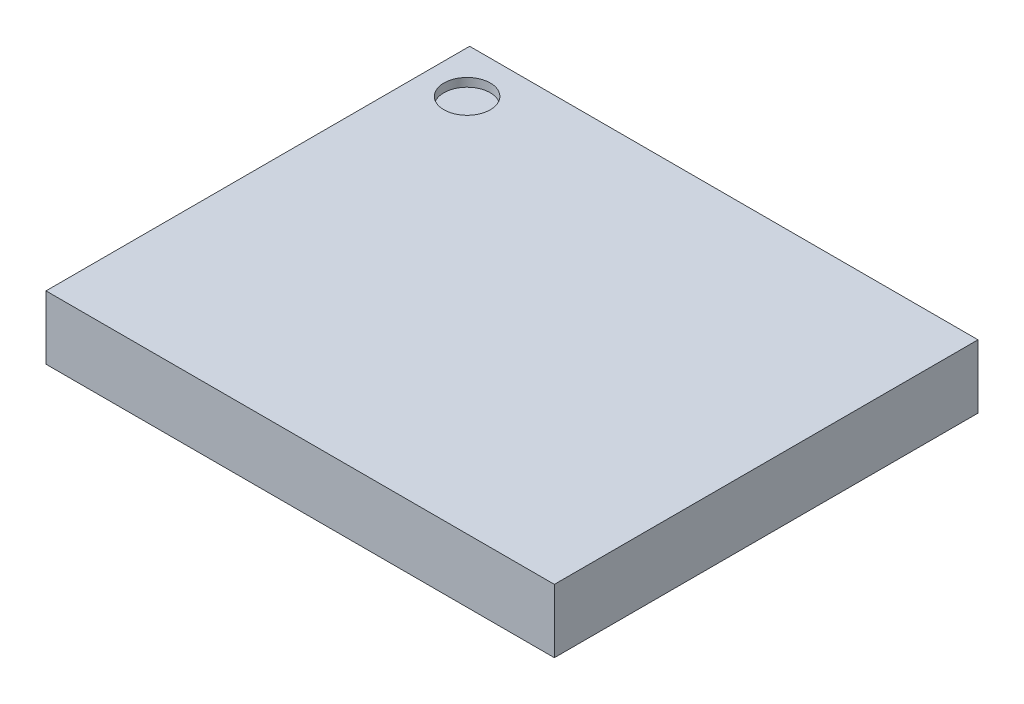
SolidWorks part; units mm, degrees
ref_plane "Front Plane" through (0, 0, 0) normal (0, 0, 1) x (1, 0, 0)
ref_plane "Top Plane" through (0, 0, 0) normal (0, 1, 0) x (1, 0, 0)
ref_plane "Right Plane" through (0, 0, 0) normal (1, 0, 0) x (0, 0, -1)
sketch "Sketch1" plane through (0, 0, 0) normal (0, 1, 0) x (1, 0, 0)
  line L1 (-3, -2.5) -> (3, -2.5)
  line L2 (-3, -2.5) -> (-3, 2.5)
  line L3 (-3, 2.5) -> (3, 2.5)
  line L4 (3, -2.5) -> (3, 2.5)
  line L5 (-3, -2.5) -> (3, 2.5) construction
  line L6 (-3, 2.5) -> (3, -2.5) construction
  point P0 (0, 0)
  dimension "D1" = 6
  dimension "D2" = 5
extrude "Boss-Extrude1" add sketch "Sketch1" along normal blind 0.75
sketch "Sketch2" plane through (0, 0.75, 0) normal (0, 1, 0) x (1, 0, 0)
  circle A0 centre (-2.5029, 1.9729) radius 0.2739
extrude "Cut-Extrude1" cut sketch "Sketch2" against normal blind 0.1
